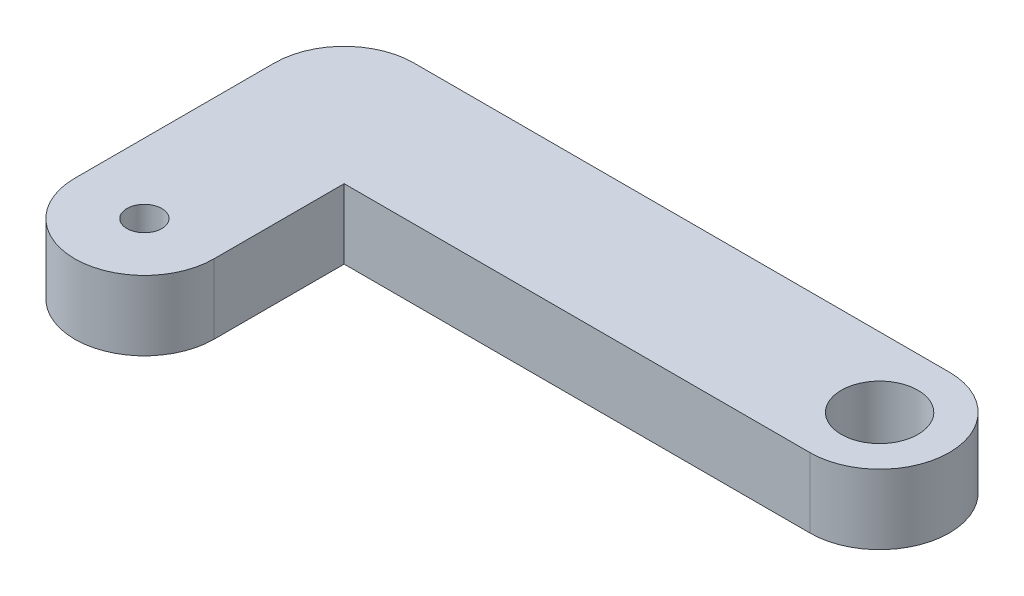
SolidWorks part; units mm, degrees
ref_plane "前视基准面" through (0, 0, 0) normal (0, 0, 1) x (1, 0, 0)
ref_plane "上视基准面" through (0, 0, 0) normal (0, 1, 0) x (1, 0, 0)
ref_plane "右视基准面" through (0, 0, 0) normal (1, 0, 0) x (0, 0, -1)
sketch "草图1" plane through (0, 0, 0) normal (0, 1, 0) x (1, 0, 0)
  line L0 (0, 0) -> (23.05, 0) construction
  line L1 (0, 3) -> (23.05, 3)
  line L2 (0, -3) -> (23.05, -3)
  arc A0 (0, 3) -> (0, -3) centre (0, 0) ccw
  arc A1 (23.05, -3) -> (23.05, 3) centre (23.05, 0) ccw
  circle A3 centre (23.05, 0) radius 1.65
  point P3 (11.525, 0)
  dimension "D2" = 3
  dimension "D3" = 3.3
  dimension "D1" = 23.05
extrude "凸台-拉伸1" add sketch "草图1" along normal blind 3
sketch "草图2" plane through (0, 0, 0) normal (0, 1, 0) x (1, 0, 0)
  line L0 (0, 0) -> (0, -8.6) construction
  line L1 (3, 0) -> (3, -8.6)
  line L2 (-3, 0) -> (-3, -8.6)
  arc A0 (3, 0) -> (-3, 0) centre (0, 0) ccw
  arc A1 (-3, -8.6) -> (3, -8.6) centre (0, -8.6) ccw
  arc A2 (0, 3) -> (0, -3) centre (0, 0) ccw construction
  point P3 (0, -4.3)
  dimension "D1" = 8.6
extrude "凸台-拉伸2" add sketch "草图2" along normal up to surface (3 mm away) up to face at (11.525, 3, 0)
sketch "草图3" plane through (0, 3, 0) normal (0, 1, 0) x (1, 0, 0)
  circle A0 centre (0, -8.6) radius 0.75
  dimension "D1" = 1.5
extrude "切除-拉伸1" cut sketch "草图3" against normal up to next
